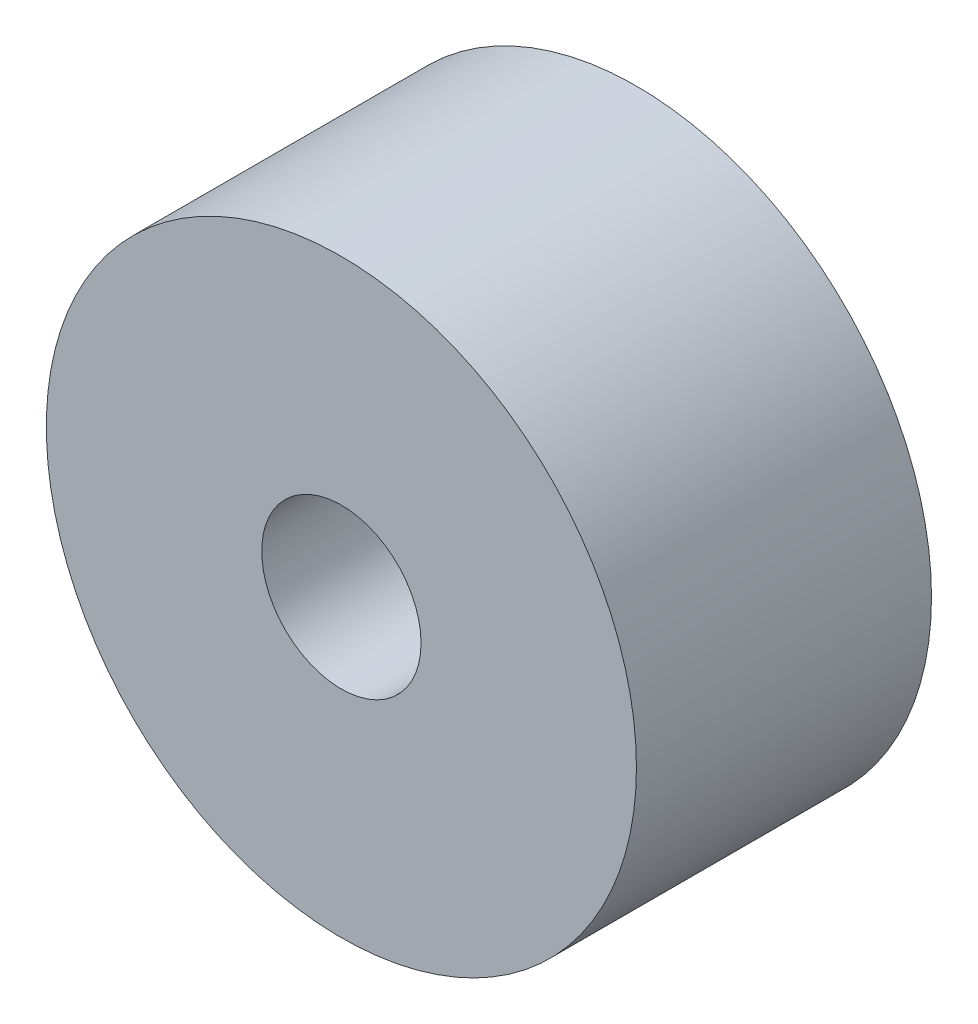
SolidWorks part; units mm, degrees
ref_plane "前视基准面" through (0, 0, 0) normal (0, 0, 1) x (1, 0, 0)
ref_plane "上视基准面" through (0, 0, 0) normal (0, 1, 0) x (1, 0, 0)
ref_plane "右视基准面" through (0, 0, 0) normal (1, 0, 0) x (0, 0, -1)
sketch "草图1" plane through (0, 0, 0) normal (0, 0, 1) x (1, 0, 0)
  circle A0 centre (0, 0) radius 2.7
  circle A1 centre (0, 0) radius 10
  dimension "D1" = 5.4
  dimension "D2" = 20
extrude "凸台-拉伸1" add sketch "草图1" along normal blind 10
